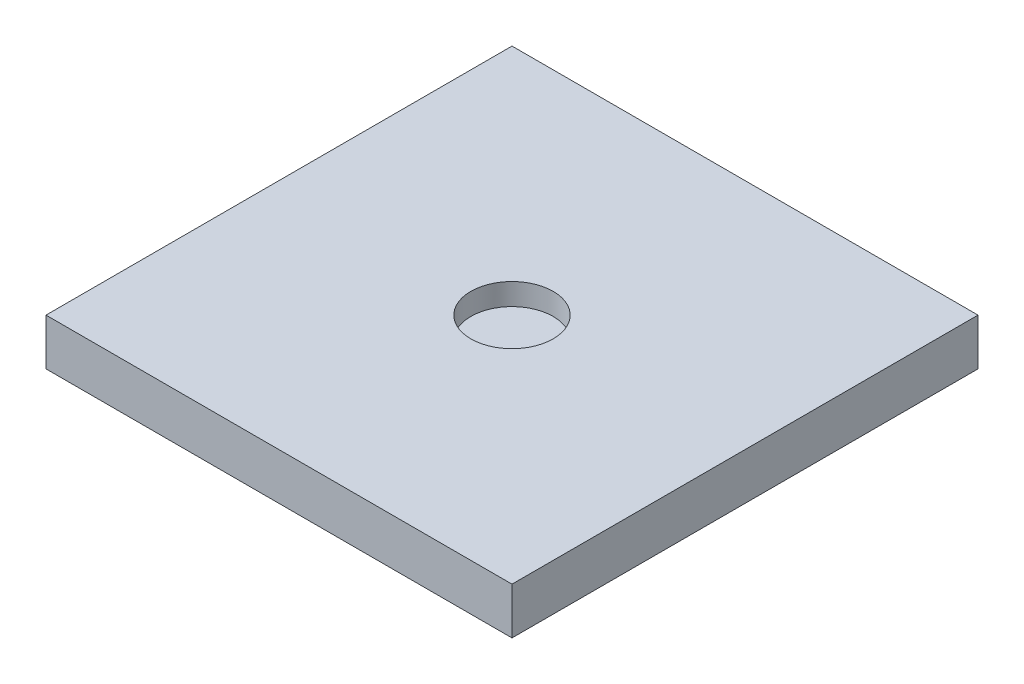
SolidWorks part; units mm, degrees
material "Pine"
ref_plane "Front Plane" through (0, 0, 0) normal (0, 0, 1) x (1, 0, 0)
ref_plane "Top Plane" through (0, 0, 0) normal (0, 1, 0) x (1, 0, 0)
ref_plane "Right Plane" through (0, 0, 0) normal (1, 0, 0) x (0, 0, -1)
sketch "Sketch1" plane through (0, 0, 0) normal (0, 1, 0) x (1, 0, 0)
  line L1 (-75, -75) -> (75, -75)
  line L2 (-75, -75) -> (-75, 75)
  line L3 (-75, 75) -> (75, 75)
  line L4 (75, -75) -> (75, 75)
  line L5 (-75, -75) -> (75, 75) construction
  line L6 (-75, 75) -> (75, -75) construction
  circle A0 centre (0, 0) radius 13.25
  point P0 (0, 0)
  dimension "D1" = 26.5
  dimension "D2" = 150
extrude "Boss-Extrude1" add sketch "Sketch1" along normal blind 15
sketch "Sketch2" plane through (0, 0, 0) normal (0, -1, 0) x (1, 0, 0)
  circle A0 centre (0, 0) radius 13.25 construction
  circle A1 centre (0, 0) radius 13.25
extrude "Boss-Extrude2" add sketch "Sketch2" against normal blind 8
